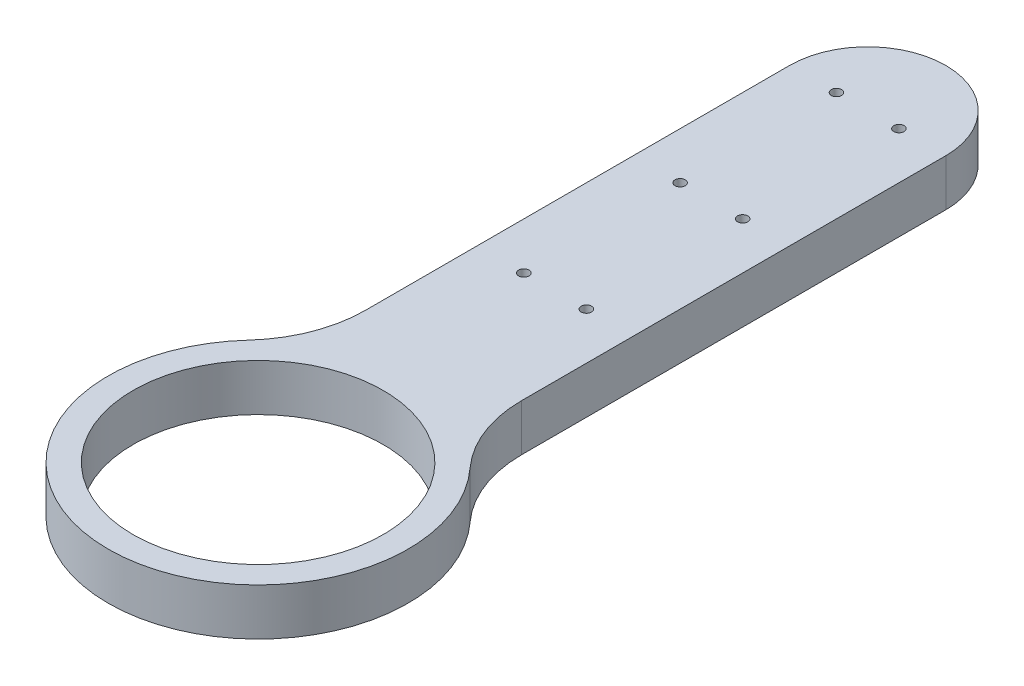
SolidWorks part; units mm, degrees
ref_plane "Front Plane" through (0, 0, 0) normal (0, 0, 1) x (1, 0, 0)
ref_plane "Top Plane" through (0, 0, 0) normal (0, 1, 0) x (1, 0, 0)
ref_plane "Right Plane" through (0, 0, 0) normal (1, 0, 0) x (0, 0, -1)
sketch "Sketch1" plane through (0, 0, 0) normal (0, 1, 0) x (1, 0, 0)
  line L0 (0, 45) -> (0, 195) construction
  line L1 (25, 59.3115) -> (25, 195)
  line L2 (25, 45) -> (25, 195) construction
  line L3 (-25, 59.3115) -> (-25, 195)
  circle A0 centre (0, 0) radius 39.9935
  arc A2 (-25, 195) -> (25, 195) centre (0, 195) cw
  arc A3 (-35.4524, 32.3497) -> (35.4524, 32.3497) centre (0, 0) ccw
  circle A5 centre (0, 0) radius 47.9935 construction
  arc A6 (35.4524, 32.3497) -> (25, 59.3115) centre (65, 59.3115) cw
  arc A7 (-25, 59.3115) -> (-35.4524, 32.3497) centre (-65, 59.3115) cw
  point P3 (0, 0)
  point P12 (45, 0)
  point P15 (45.8964, 14.0319)
  point P19 (25, 40.968)
  dimension "D1" = 79.987
  dimension "D3" = 150
  dimension "D5" = 40
  dimension "D2" = 8
  dimension "D4" = 25
extrude "Boss-Extrude1" add sketch "Sketch1" along normal blind 15
sketch "Sketch2" plane through (0, 0, 0) normal (0, -1, 0) x (1, 0, 0)
  line L0 (0, -195) -> (0, -45) construction
  line L1 (10, -195) -> (10, -45) construction
  line L2 (-10, -195) -> (-10, -45) construction
  line L3 (-10, -95) -> (10, -95) construction
  line L4 (-10, -145) -> (10, -145) construction
  line L5 (-10, -195) -> (10, -195) construction
  circle A0 centre (10, -95) radius 1.65
  circle A1 centre (-10, -95) radius 1.65
  circle A2 centre (10, -145) radius 1.65
  circle A3 centre (-10, -145) radius 1.65
  circle A4 centre (10, -195) radius 1.65
  circle A5 centre (-10, -195) radius 1.65
  dimension "D4" = 3.3
  dimension "D5" = 3.3
  dimension "D1" = 150
  dimension "D3" = 50
  dimension "D2" = 10
  dimension "D6" = 3
extrude "Cut-Extrude1" cut sketch "Sketch2" against normal blind 15
